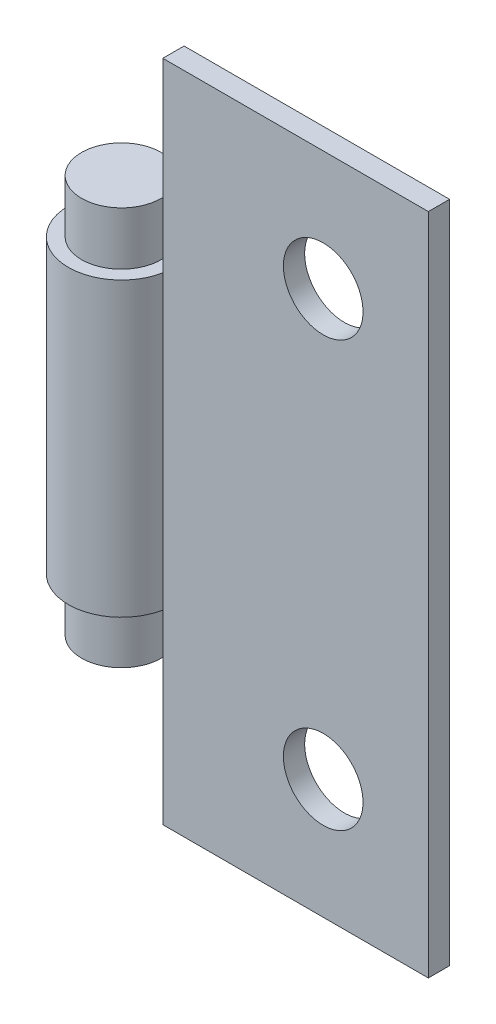
SolidWorks part; units mm, degrees
ref_plane "前视基准面" through (0, 0, 0) normal (0, 0, 1) x (1, 0, 0)
ref_plane "上视基准面" through (0, 0, 0) normal (0, 1, 0) x (1, 0, 0)
ref_plane "右视基准面" through (0, 0, 0) normal (1, 0, 0) x (0, 0, -1)
other "Configuration Table"
sketch "草图1" plane through (0, 0, 0) normal (0, 0, 1) x (1, 0, 0)
  line L1 (-5, -12.5) -> (5, -12.5)
  line L2 (-5, -12.5) -> (-5, 12.5)
  line L3 (-5, 12.5) -> (5, 12.5)
  line L4 (5, -12.5) -> (5, 12.5)
  line L5 (-5, -12.5) -> (5, 12.5) construction
  line L6 (-5, 12.5) -> (5, -12.5) construction
  point P0 (0, 0)
  dimension "D1" = 10
  dimension "D2" = 25
extrude "凸台-拉伸1" add sketch "草图1" along normal blind 0.8
ref_plane "基准面1" through (0, 0, 0.4) normal (0, 0, -1) x (-1, 0, 0)
sketch "草图4" plane through (0, 0, 0) normal (0, 1, 0) x (1, 0, 0)
  circle A0 centre (-6.9596, -0.4) radius 2
  dimension "D1" = 4
extrude "凸台-拉伸2" add sketch "草图4" along normal mid plane 11
sketch "草图5" plane through (0, 5.5, 0) normal (0, 1, 0) x (1, 0, 0)
  circle A0 centre (-6.9596, -0.4) radius 1.5
  dimension "D1" = 3
extrude "凸台-拉伸3" add sketch "草图5" along normal mid plane 4
mirror "镜向1" about plane through (0, 0, 0) normal (0, 1, 0) of "凸台-拉伸3"
sketch "草图6" plane through (0, 0, 0) normal (0, 0, -1) x (-1, 0, 0)
  line L0 (6.9596, 7.5) -> (6.9596, 10.2546) construction
  line L1 (8.4596, 7.5) -> (5.4596, 7.5) construction
  line L2 (-1.0404, 12.5) -> (-1.0404, 50012.5) construction
  line L4 (-5, 12.5) -> (5, 12.5) construction
  circle A0 centre (-1.0404, 8) radius 1.5
  circle A1 centre (-1.0404, -8) radius 1.5
  dimension "D2" = 3
  dimension "D3" = 4.5
  dimension "D4" = 16
  dimension "D5" = 3
  dimension "D1" = 8
extrude "切除-拉伸1" cut sketch "草图6" against normal blind 4
